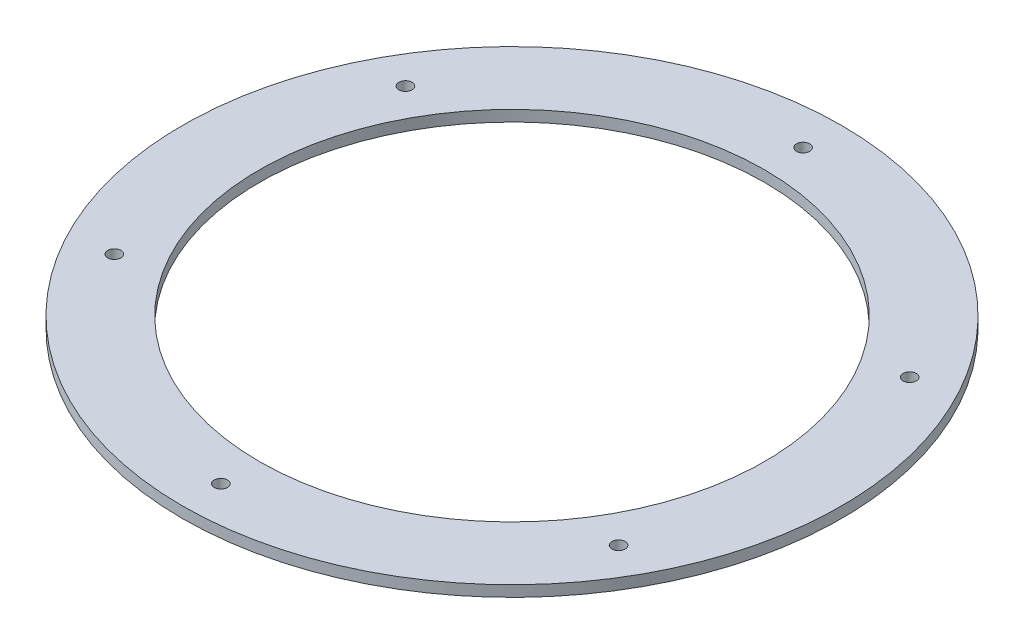
SolidWorks part; units mm, degrees
material "1023 Carbon Steel Sheet (SS)"
ref_plane "Front Plane" through (0, 0, 0) normal (0, 0, 1) x (1, 0, 0)
ref_plane "Top Plane" through (0, 0, 0) normal (0, 1, 0) x (1, 0, 0)
ref_plane "Right Plane" through (0, 0, 0) normal (1, 0, 0) x (0, 0, -1)
sketch "Sketch1" plane through (0, 0, 0) normal (0, 1, 0) x (1, 0, 0)
  line L0 (0, 150) -> (0, 132.5) construction
  line L1 (0, 132.5) -> (0, 115) construction
  circle A0 centre (0, 0) radius 150
  circle A1 centre (0, 0) radius 115
  circle A2 centre (0, 0) radius 132.5 construction
  circle A3 centre (0, 132.5) radius 3
  circle A4 centre (114.7484, 66.25) radius 3
  circle A5 centre (114.7484, -66.25) radius 3
  circle A6 centre (0, -132.5) radius 3
  circle A7 centre (-114.7484, -66.25) radius 3
  circle A8 centre (-114.7484, 66.25) radius 3
  point P22 (0, 0)
  dimension "D1" = 6
  dimension "D2" = 230
  dimension "D3" = 300
  dimension "D4" = 6
extrude "Boss-Extrude1" add sketch "Sketch1" along normal blind 5
